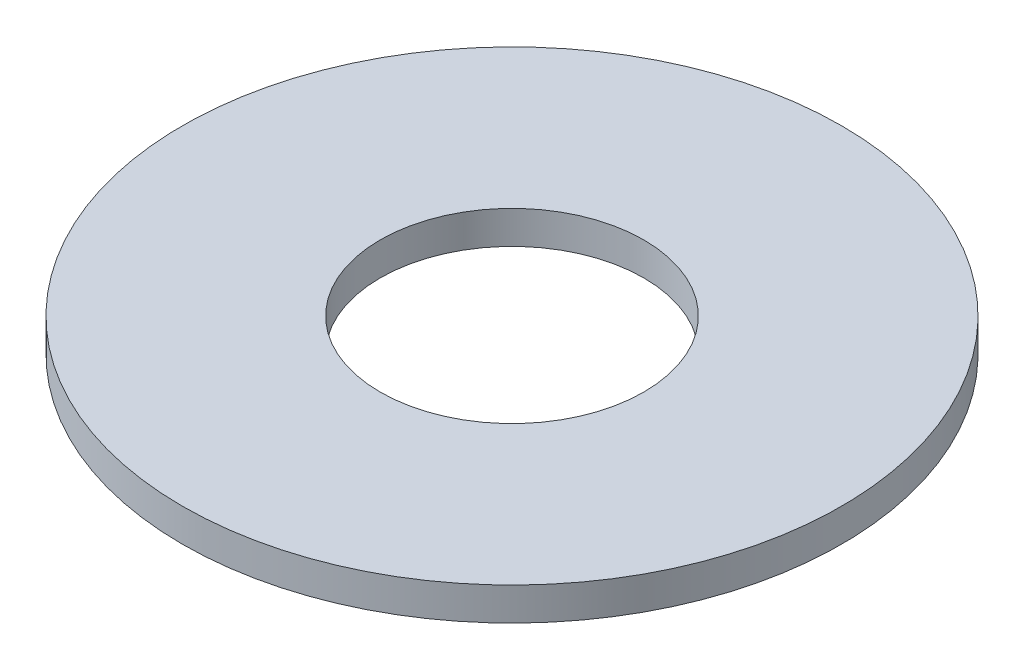
SolidWorks part; units mm, degrees
ref_plane "Front Plane" through (0, 0, 0) normal (0, 0, 1) x (1, 0, 0)
ref_plane "Top Plane" through (0, 0, 0) normal (0, 1, 0) x (1, 0, 0)
ref_plane "Right Plane" through (0, 0, 0) normal (1, 0, 0) x (0, 0, -1)
sketch "Sketch1" plane through (0, 0, 0) normal (0, 1, 0) x (1, 0, 0)
  circle A0 centre (0, 0) radius 10
  circle A1 centre (0, 0) radius 4
  dimension "D1" = 20
  dimension "D2" = 8
extrude "Boss-Extrude1" add sketch "Sketch1" along normal blind 1
